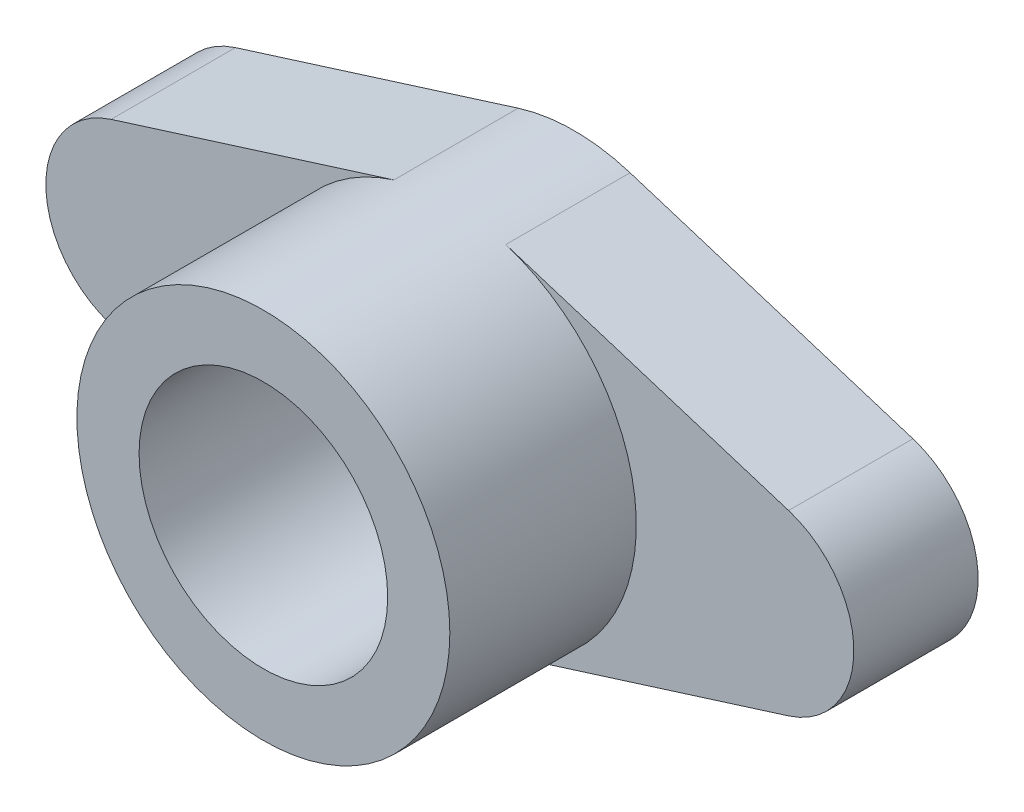
SolidWorks part; units mm, degrees
ref_plane "Front Plane" through (0, 0, 0) normal (0, 0, 1) x (1, 0, 0)
ref_plane "Top Plane" through (0, 0, 0) normal (0, 1, 0) x (1, 0, 0)
ref_plane "Right Plane" through (0, 0, 0) normal (1, 0, 0) x (0, 0, -1)
sketch "Sketch1" plane through (0, 0, 0) normal (0, 0, 1) x (1, 0, 0)
  line L0 (0, 57.8173) -> (0, -108.1339) construction
  line L1 (-142.6476, 0) -> (157.3524, 0) construction
  line L2 (-9, 28.6182) -> (-54.5, 14.3091)
  line L3 (-54.5, -14.3091) -> (-9, -28.6182)
  line L4 (9, -28.6182) -> (54.5, -14.3091)
  line L5 (9, 28.6182) -> (54.5, 14.3091)
  circle A0 centre (0, 0) radius 20
  arc A1 (9, 28.6182) -> (-9, 28.6182) centre (0, 0) ccw
  arc A2 (-54.5, 14.3091) -> (-54.5, -14.3091) centre (-50, 0) ccw
  arc A3 (54.5, -14.3091) -> (54.5, 14.3091) centre (50, 0) ccw
  arc A4 (-9, -28.6182) -> (9, -28.6182) centre (0, 0) ccw
  dimension "D1" = 40
  dimension "D2" = 60
  dimension "D3" = 30
  dimension "D4" = 30
  dimension "D5" = 50
  dimension "D6" = 100
extrude "Boss-Extrude1" add sketch "Sketch1" along normal blind 20
sketch "Sketch2" plane through (0, 0, 20) normal (0, 0, 1) x (1, 0, 0)
  circle A0 centre (0, 0) radius 30
  circle A1 centre (0, 0) radius 20
  dimension "D1" = 60
extrude "Boss-Extrude2" add sketch "Sketch2" along normal blind 30
